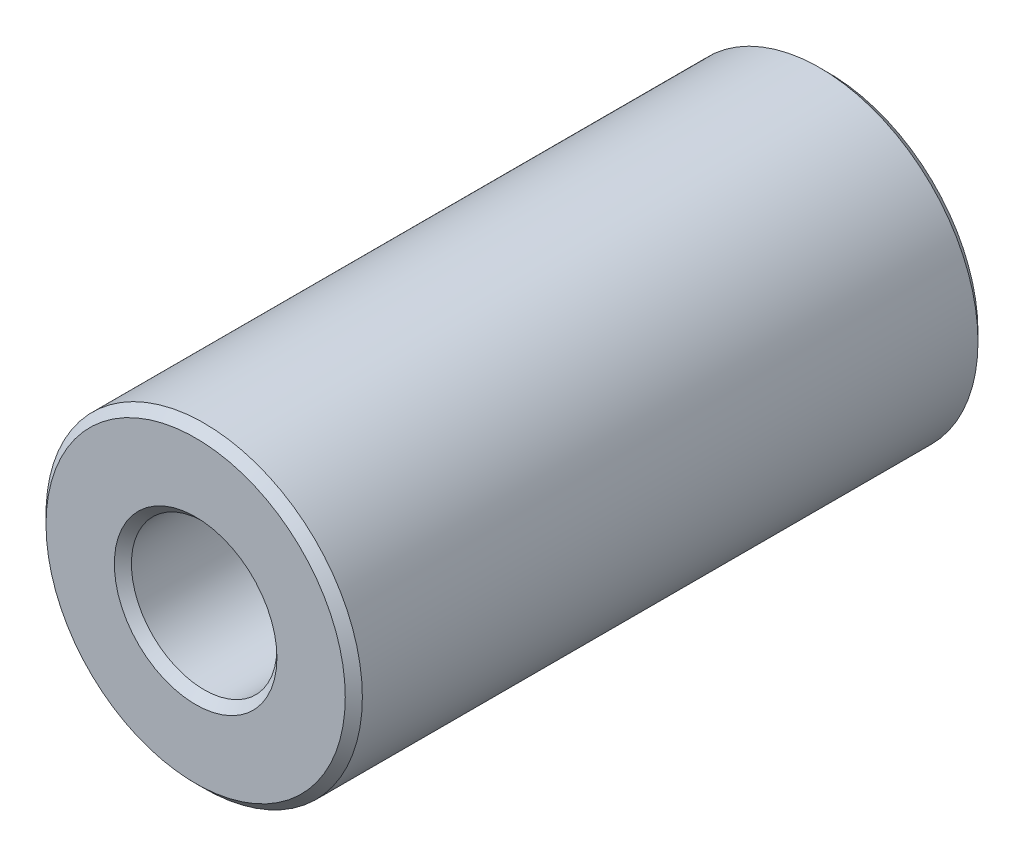
SolidWorks part; units mm, degrees
ref_plane "Front Plane" through (0, 0, 0) normal (0, 0, 1) x (1, 0, 0)
ref_plane "Top Plane" through (0, 0, 0) normal (0, 1, 0) x (1, 0, 0)
ref_plane "Right Plane" through (0, 0, 0) normal (1, 0, 0) x (0, 0, -1)
sketch "Sketch1" plane through (0, 0, 0) normal (0, 0, 1) x (1, 0, 0)
  circle A0 centre (0, 0) radius 3.175 construction
  circle A1 centre (0, 0) radius 1.4605 construction
  point P4 (0, 3.175)
  dimension "ID" = 2.921
  dimension "OD" = 6.35
sketch "Sketch2" plane through (0, 0, 0) normal (1, 0, 0) x (0, 0, -1)
  line L0 (-6.35, 3.175) -> (6.35, 3.175) construction
  dimension "Length" = 12.7
sketch "Sketch3" plane through (0, 0, 0) normal (0, 0, 1) x (1, 0, 0)
  circle A0 centre (0, 0) radius 1.4605 construction
  circle A1 centre (0, 0) radius 3.175 construction
  circle A2 centre (0, 0) radius 1.4605
  circle A3 centre (0, 0) radius 3.175
extrude "Boss-Extrude1" add sketch "Sketch3" against normal up to vertex (6.35 mm away) and the other way up to vertex (6.35 mm away) up to point (0, 3.175, -6.35) other way up to point (0, 3.175, 6.35)
chamfer "Chamfer1" distance 0.1714 angle 45 1 edges at (3.175, 0, 6.35)
equation "\"D1@Chamfer1\"=(\"OD@Sketch1\"-\"ID@Sketch1\")*0.05"
